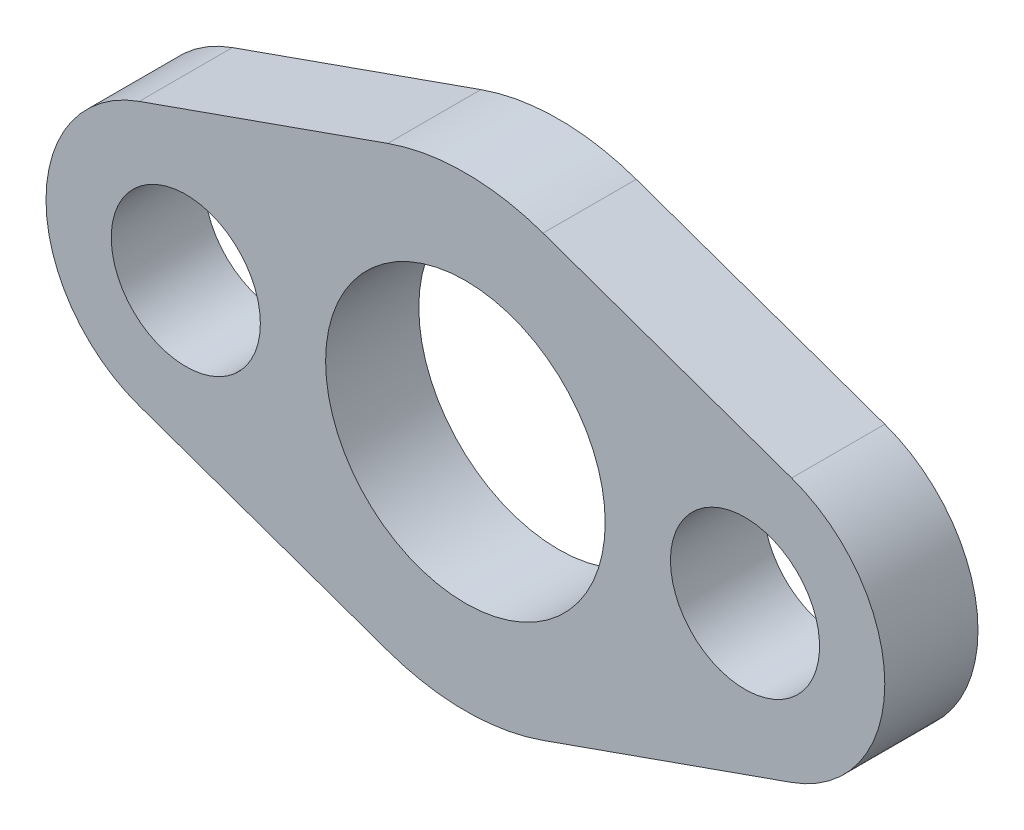
SolidWorks part; units mm, degrees
ref_plane "Front Plane" through (0, 0, 0) normal (0, 0, 1) x (1, 0, 0)
ref_plane "Top Plane" through (0, 0, 0) normal (0, 1, 0) x (1, 0, 0)
ref_plane "Right Plane" through (0, 0, 0) normal (1, 0, 0) x (0, 0, -1)
sketch "Sketch1" plane through (0, 0, 0) normal (0, 0, 1) x (1, 0, 0)
  line L0 (-5, 14.1421) -> (21.6667, 23.5702)
  line L2 (-5, -14.1421) -> (21.6667, -23.5702)
  line L3 (65, -14.1421) -> (38.3333, -23.5702)
  line L4 (65, 14.1421) -> (38.3333, 23.5702)
  line L5 (30, 0) -> (30, -15) construction
  circle A0 centre (0, 0) radius 8
  arc A1 (-5, 14.1421) -> (-5, -14.1421) centre (0, 0) ccw
  circle A2 centre (30, 0) radius 15
  arc A3 (21.6667, -23.5702) -> (38.3333, -23.5702) centre (30, 0) ccw
  arc A4 (65, 14.1421) -> (65, -14.1421) centre (60, 0) cw
  circle A5 centre (60, 0) radius 8
  arc A6 (38.3333, 23.5702) -> (21.6667, 23.5702) centre (30, 0) ccw
  dimension "D1" = 30
  dimension "D2" = 16
  dimension "D3" = 30
  dimension "D4" = 25
  dimension "D5" = 60
extrude "Boss-Extrude1" add sketch "Sketch1" along normal blind 10
